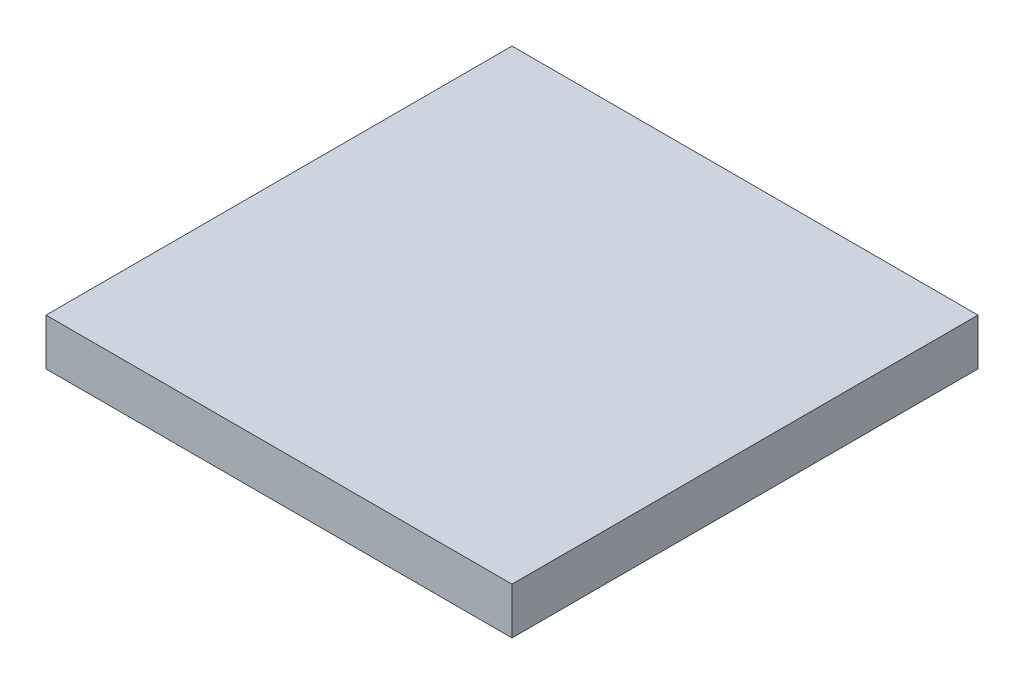
SolidWorks part; units mm, degrees
ref_plane "Front Plane" through (0, 0, 0) normal (0, 0, 1) x (1, 0, 0)
ref_plane "Top Plane" through (0, 0, 0) normal (0, 1, 0) x (1, 0, 0)
ref_plane "Right Plane" through (0, 0, 0) normal (1, 0, 0) x (0, 0, -1)
sketch "Sketch1" plane through (0, 0, 0) normal (0, 1, 0) x (1, 0, 0)
  line L1 (-75, -75) -> (75, -75)
  line L2 (-75, -75) -> (-75, 75)
  line L3 (-75, 75) -> (75, 75)
  line L4 (75, -75) -> (75, 75)
  line L5 (-75, -75) -> (75, 75) construction
  line L6 (-75, 75) -> (75, -75) construction
  point P1 (0, 0)
  dimension "D1" = 150
  dimension "D2" = 150
extrude "Boss-Extrude1" add sketch "Sketch1" along normal blind 15
